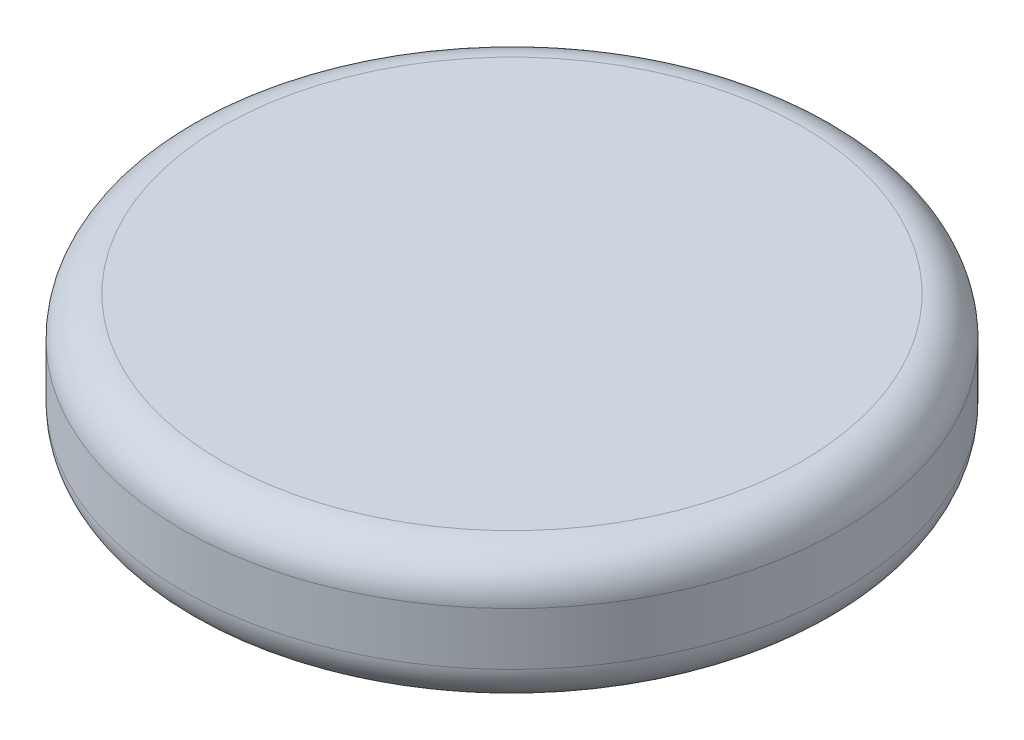
SolidWorks part; units mm, degrees
material "Custom Plastic"
ref_plane "Front Plane" through (0, 0, 0) normal (0, 0, 1) x (1, 0, 0)
ref_plane "Top Plane" through (0, 0, 0) normal (0, 1, 0) x (1, 0, 0)
ref_plane "Right Plane" through (0, 0, 0) normal (1, 0, 0) x (0, 0, -1)
sketch "Sketch2" plane through (0, 0, 0) normal (0, 1, 0) x (1, 0, 0)
  circle A0 centre (0, 0) radius 25
  dimension "D1" = 50
extrude "Boss-Extrude1" add sketch "Sketch2" along normal blind 10
fillet "Fillet1" radius 3 2 edges at (0, 0, 25) (0, 10, 25)
sketch "Sketch3" plane through (0, 0, 0) normal (0, -1, 0) x (-1, 0, 0)
  line L1 (-14.125, -14.125) -> (14.125, -14.125)
  line L2 (-14.125, -14.125) -> (-14.125, 14.125)
  line L3 (-14.125, 14.125) -> (14.125, 14.125)
  line L4 (14.125, -14.125) -> (14.125, 14.125)
  line L5 (-14.125, -14.125) -> (14.125, 14.125) construction
  line L6 (-14.125, 14.125) -> (14.125, -14.125) construction
  point P0 (0, 0)
  dimension "D1" = 28.25
extrude "Boss-Extrude2" add sketch "Sketch3" along normal blind 1
sketch "Sketch4" plane through (0, 10, 0) normal (0, 1, 0) x (1, 0, 0)
  text T0 "GPS"
  dimension "D1" = 5
